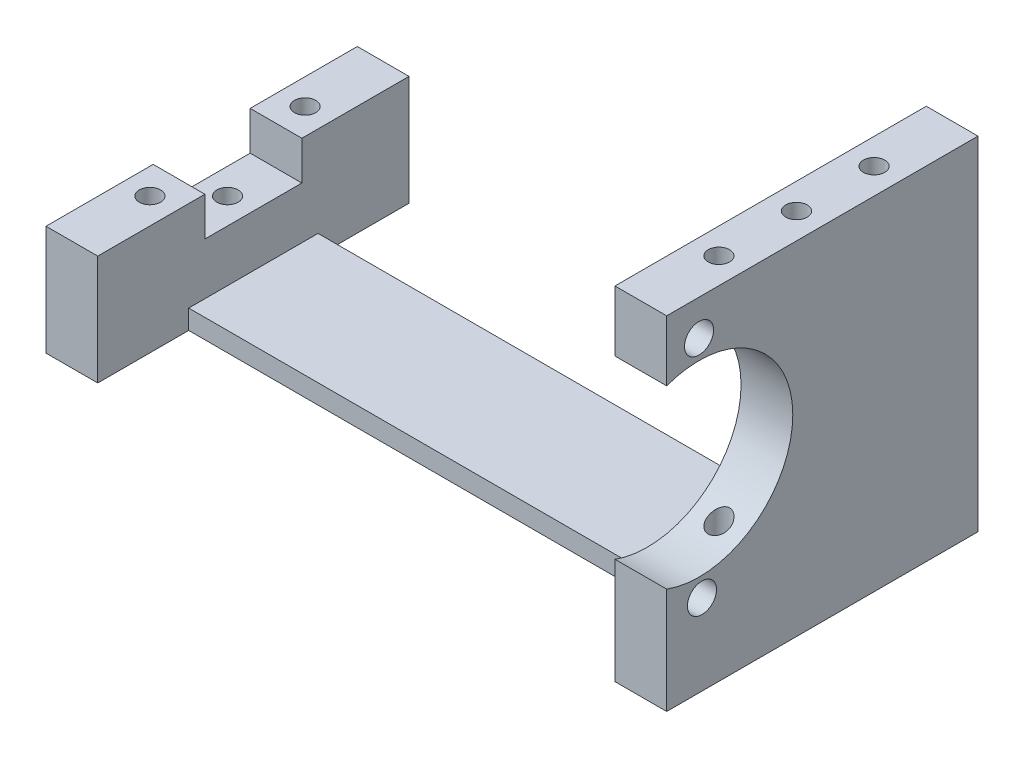
SolidWorks part; units mm, degrees
ref_plane "前视基准面" through (0, 0, 0) normal (0, 0, 1) x (1, 0, 0)
ref_plane "上视基准面" through (0, 0, 0) normal (0, 1, 0) x (1, 0, 0)
ref_plane "右视基准面" through (0, 0, 0) normal (1, 0, 0) x (0, 0, -1)
sketch "草图1" plane through (0, 0, 0) normal (0, 1, 0) x (1, 0, 0)
  line L0 (0, -4.5759) -> (0, 4.5759) construction
  line L1 (-52.9759, 0) -> (52.9759, 0) construction
  line L2 (48, -24.0737) -> (40, -24.0737)
  line L3 (-48, -24.0737) -> (-40, -24.0737)
  line L4 (-48, -24.0737) -> (-48, 24.0737)
  line L5 (-48, 24.0737) -> (-40, 24.0737)
  line L6 (-40, -24.0737) -> (-40, 24.0737)
  line L7 (-48, -24.0737) -> (-40, 24.0737) construction
  line L8 (-48, 24.0737) -> (-40, -24.0737) construction
  line L9 (40, -24.0737) -> (40, 24.0737)
  line L10 (48, 24.0737) -> (40, 24.0737)
  line L11 (48, -24.0737) -> (48, 24.0737)
  circle A0 centre (-44, 0) radius 1.65
  circle A1 centre (44, 0) radius 1.65
  circle A2 centre (-44, -12) radius 1.65
  circle A3 centre (44, -12) radius 1.65
  circle A4 centre (44, 12) radius 1.65
  circle A5 centre (-44, 12) radius 1.65
  dimension "D1" = 88
  dimension "D2" = 12
  dimension "D3" = 3.3
  dimension "D4" = 3.3
  dimension "D5" = 8
extrude "凸台-拉伸1" add sketch "草图1" along normal blind 53
sketch "草图2" plane through (-40, 0, 0) normal (1, 0, 0) x (0, 0, -1)
  line L5 (-10, 3) -> (-10, 0)
  line L6 (-10, 3) -> (10, 3)
  line L7 (-10, 0) -> (10, 0)
  line L8 (10, 3) -> (10, 0)
  line L9 (-10, 3) -> (10, 0) construction
  line L10 (-10, 0) -> (10, 3) construction
  line L11 (-24.0737, 0) -> (24.0737, 0) construction
  point P1 (0, 1.5)
  dimension "D1" = 3
  dimension "D2" = 20
extrude "凸台-拉伸2" add sketch "草图2" along normal up to surface (80 mm away) up to face at (40, 26.5, 0)
sketch "草图3" plane through (48, 0, 0) normal (1, 0, 0) x (0, 0, -1)
  line L0 (-24.0737, 0) -> (24.0737, 0) construction
  line L1 (-24.0737, 53) -> (-24.0737, 0) construction
  line L2 (-19.0737, 30) -> (8.5188, 30.3594) construction
  circle A0 centre (-19.0737, 30) radius 14.5
  circle A1 centre (-19.0737, 47.5) radius 2.25
  circle A2 centre (-18.618, 12.5059) radius 2.25
  dimension "D1" = 29
  dimension "D4" = 4.5
  dimension "D5" = 17.5
  dimension "D2" = 30
  dimension "D3" = 5
extrude "切除-拉伸1" cut sketch "草图3" against normal blind 20
sketch "草图4" plane through (-48, 0, 0) normal (-1, 0, 0) x (0, 0, 1)
  line L0 (24.0737, 53) -> (24.0737, 0) construction
  line L1 (-24.0737, 53) -> (24.0737, 53)
  line L2 (-24.0737, 53) -> (-24.0737, 17)
  line L3 (-24.0737, 17) -> (24.0737, 17)
  line L4 (24.0737, 53) -> (24.0737, 17)
  dimension "D1" = 36
extrude "切除-拉伸2" cut sketch "草图4" against normal blind 15
sketch "草图6" plane through (0, 17, 0) normal (0, 1, 0) x (1, 0, 0)
  line L0 (-40, 24.0737) -> (-40, -24.0737) construction
  line L1 (-48, -7.5) -> (-40, -7.5)
  line L2 (-48, -7.5) -> (-48, 7.5)
  line L3 (-48, 7.5) -> (-40, 7.5)
  line L4 (-40, -7.5) -> (-40, 7.5)
  line L5 (-48, -7.5) -> (-40, 7.5) construction
  line L6 (-48, 7.5) -> (-40, -7.5) construction
  point P0 (-44, 0)
  dimension "D1" = 15
extrude "切除-拉伸4" cut sketch "草图6" against normal blind 6
